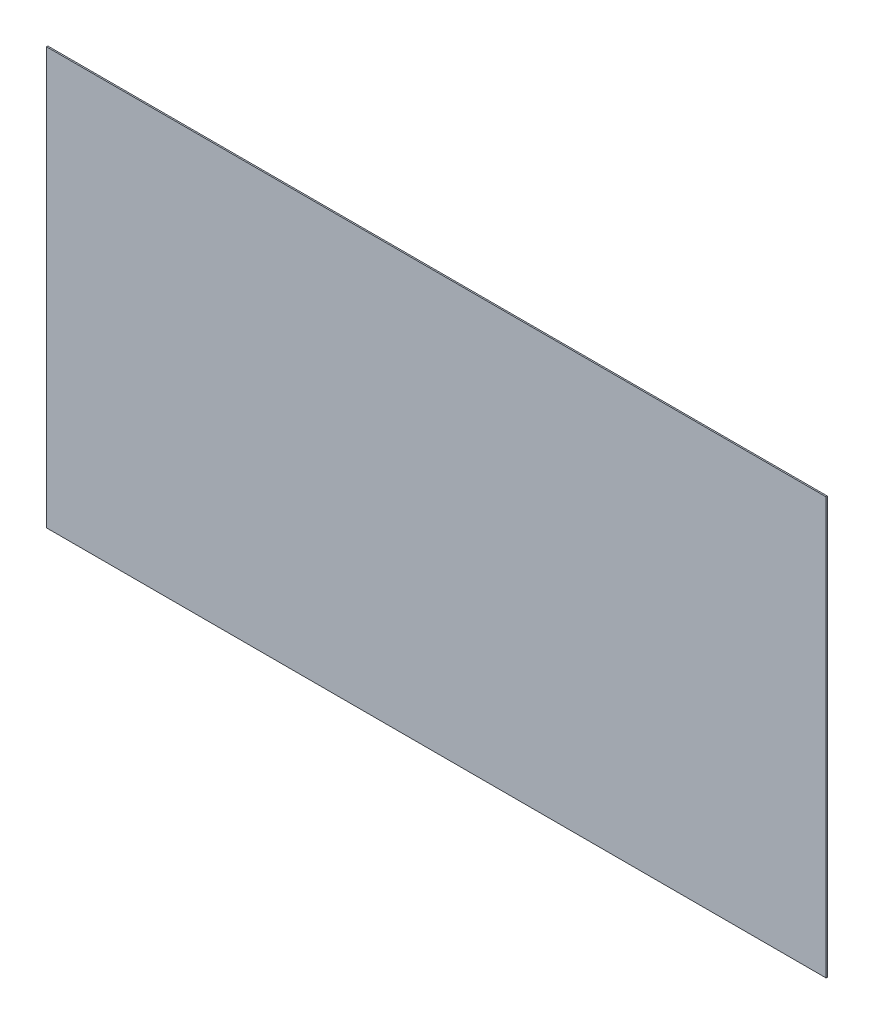
SolidWorks part; units mm, degrees
ref_plane "Front Plane" through (0, 0, 0) normal (0, 0, 1) x (1, 0, 0)
ref_plane "Top Plane" through (0, 0, 0) normal (0, 1, 0) x (1, 0, 0)
ref_plane "Right Plane" through (0, 0, 0) normal (1, 0, 0) x (0, 0, -1)
sketch "Sketch1" plane through (0, 0, 325.4102) normal (0, 0, 1) x (1, 0, 0)
  line L8 (290, -190) -> (-290, -190)
  line L9 (-290, -190) -> (-290, -500)
  line L10 (-290, -500) -> (290, -500)
  line L11 (290, -500) -> (290, -190)
  line L12 (290, -190) -> (-290, -190)
  line L13 (-290, -190) -> (-290, -500)
  line L14 (-290, -500) -> (290, -500)
  line L15 (290, -500) -> (290, -190)
  dimension "D1" = 10
extrude "Boss-Extrude1" add sketch "Sketch1" along normal blind 1
